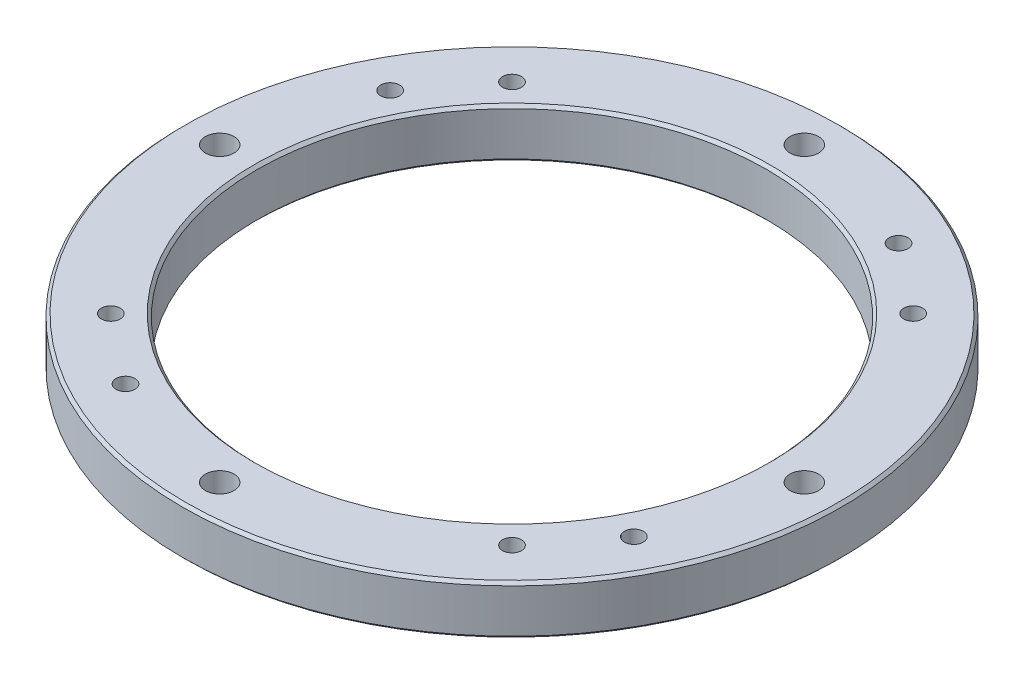
SolidWorks part; units mm, degrees
material "6061 合金"
ref_plane "正面" through (0, 0, 0) normal (0, 0, 1) x (1, 0, 0)
ref_plane "平面" through (0, 0, 0) normal (0, 1, 0) x (1, 0, 0)
ref_plane "右側面" through (0, 0, 0) normal (1, 0, 0) x (0, 0, -1)
sketch "ｽｹｯﾁ1" plane through (0, 0, 0) normal (0, 1, 0) x (1, 0, 0)
  circle A0 centre (0, 0) radius 57.5
  circle A1 centre (0, 0) radius 44.5
  dimension "D1" = 115
  dimension "D2" = 89
extrude "ﾎﾞｽ - 押し出し1" add sketch "ｽｹｯﾁ1" along normal blind 8.6
sketch "ｽｹｯﾁ2" plane through (0, 8.6, 0) normal (0, 1, 0) x (1, 0, 0)
  circle A0 centre (0, 0) radius 51 construction
  circle A1 centre (-51, 0) radius 2.5
  circle A2 centre (0, 51) radius 2.5
  circle A3 centre (51, 0) radius 2.5
  circle A4 centre (0, -51) radius 2.5
  point P14 (0, 0)
  dimension "D1" = 102
  dimension "D2" = 5
  dimension "D3" = 4
extrude "ｶｯﾄ - 押し出し1" cut sketch "ｽｹｯﾁ2" against normal through all
chamfer "面取り1" distance 0.5 angle 45 4 edges at (0, 8.6, 57.5) (0, 0, 57.5) (0, 0, 44.5) (0, 8.6, 44.5)
sketch "ｽｹｯﾁ3" plane through (0, 8.6, 0) normal (0, 1, 0) x (1, 0, 0)
  line L0 (0, 0) -> (0, -57) construction
  line L1 (0, 0) -> (-57, 0) construction
  line L2 (0, 0) -> (23.0874, 44.3505) construction
  circle A0 centre (0, 0) radius 57 construction
  circle A1 centre (-35, 35) radius 1.65
  circle A2 centre (-35, -35) radius 1.65
  circle A3 centre (35, -35) radius 1.65
  circle A4 centre (35, 35) radius 1.65
  circle A5 centre (23.0874, 44.3505) radius 1.65
  circle A6 centre (44.3505, -23.0874) radius 1.65
  circle A7 centre (-23.0874, -44.3505) radius 1.65
  circle A8 centre (-44.3505, 23.0874) radius 1.65
  point P17 (55.7927, -35)
  point P18 (0, 0)
  point P26 (0, 0)
  dimension "D1" = 3.3
  dimension "D2" = 70
  dimension "D3" = 70
  dimension "D6" = 3.3
  dimension "D4" = 152.5
  dimension "D5" = 50
  dimension "D7" = 4
extrude "ｶｯﾄ - 押し出し2" cut sketch "ｽｹｯﾁ3" against normal through all
